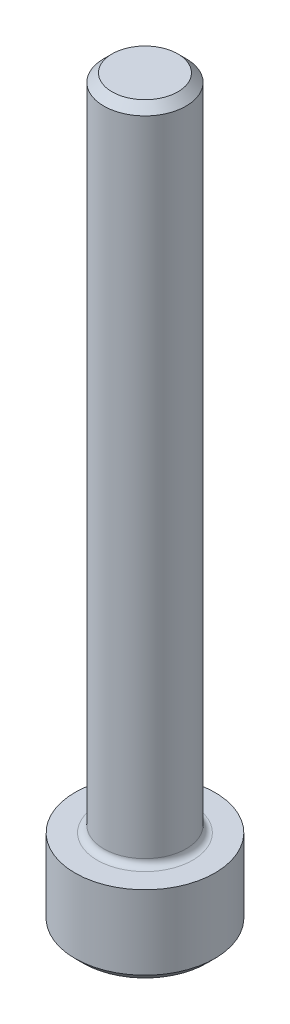
SolidWorks part; units mm, degrees
ref_plane "Front Plane" through (0, 0, 0) normal (0, 0, 1) x (1, 0, 0)
ref_plane "Top Plane" through (0, 0, 0) normal (0, 1, 0) x (1, 0, 0)
ref_plane "Right Plane" through (0, 0, 0) normal (1, 0, 0) x (0, 0, -1)
sketch "Sketch2" plane through (0, 0, 0) normal (0, 1, 0) x (1, 0, 0)
  circle A0 centre (0, 0) radius 2.5
extrude "Boss-Extrude1" add sketch "Sketch2" along normal blind 40
sketch "Sketch3" plane through (0, 0, 0) normal (0, 1, 0) x (1, 0, 0)
  circle A0 centre (0, 0) radius 4.25
extrude "Boss-Extrude2" add sketch "Sketch3" against normal blind 5
fillet "Fillet1" radius 0.4 1 edges at (0, 0, 2.5)
chamfer "Chamfer1" distance 0.5 angle 45 2 edges at (0, 40, 2.5) (0, -5, 4.25)
sketch "Sketch4" plane through (0, -5, 0) normal (0, -1, 0) x (1, 0, 0)
  line L1 (0, 2.3094) -> (-2, 1.1547)
  line L2 (-2, 1.1547) -> (-2, -1.1547)
  line L3 (-2, -1.1547) -> (0, -2.3094)
  line L4 (0, -2.3094) -> (2, -1.1547)
  line L5 (2, -1.1547) -> (2, 1.1547)
  line L6 (2, 1.1547) -> (0, 2.3094)
  circle A0 centre (0, 0) radius 2 construction
extrude "Cut-Extrude1" cut sketch "Sketch4" against normal blind 2.5
